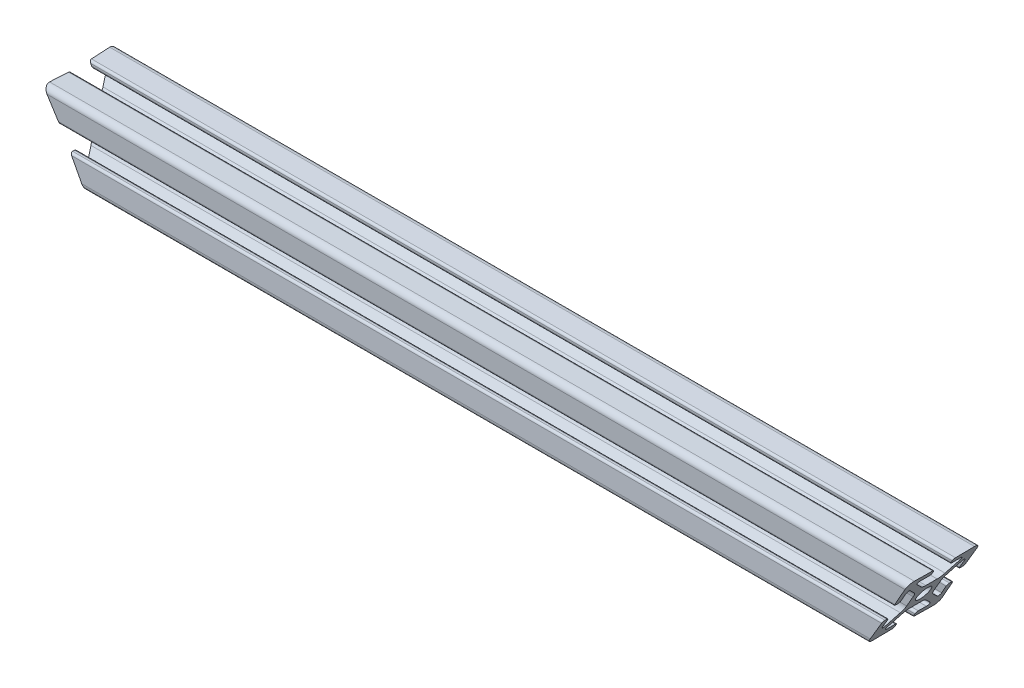
SolidWorks part; units mm, degrees
material "6061-T6 (SS)"
ref_plane "Front Plane" through (0, 0, 0) normal (0, 0, 1) x (1, 0, 0)
ref_plane "Top Plane" through (0, 0, 0) normal (0, 1, 0) x (1, 0, 0)
ref_plane "Right Plane" through (0, 0, 0) normal (1, 0, 0) x (0, 0, -1)
sketch "Sketch1" plane through (0, 0, 0) normal (1, 0, 0) x (0, 0, -1)
  line L0 (0, -12.7) -> (0, 12.7) construction
  line L1 (-7.874, 12.7) -> (7.874, 12.7) construction
  line L2 (-12.7, 0) -> (12.7, 0) construction
  line L3 (-7.874, 12.7) -> (-7.874, 4.826) construction
  line L4 (-3.302, 12.7) -> (3.302, 12.7) construction
  line L5 (-12.7, -12.7) -> (12.7, -12.7) construction
  line L6 (-12.7, 12.7) -> (12.7, 12.7) construction
  circle A0 centre (0, 0) radius 2.54 construction
  point P7 (0, 12.7)
  point P10 (0, 0)
  point P13 (0, 0)
  point P16 (0, 12.7)
  point P17 (-3.302, 12.7)
  point P18 (3.302, 12.7)
  point P21 (0, -12.7)
  point P24 (0, 12.7)
  dimension "Center Hole Diameter" = 5.08
  dimension "Rail Width" = 25.4
  dimension "Rail Height" = 25.4
  dimension "T-Slot Depth" = 7.874
  dimension "D1" = 15.748
  dimension "T-Slot Width" = 6.604
  dimension "D2" = 12.7
sketch "Sketch2" plane through (0, 0, 0) normal (0, 0, 1) x (1, 0, 0)
  line L0 (-152.4, 0) -> (152.4, 0) construction
  line L1 (0, 0) -> (0, 26.104) construction
  line L2 (152.4, -12.7) -> (152.4, 12.7) construction
  line L3 (-152.4, -12.7) -> (-152.4, 12.7) construction
  point P3 (-114.3, 0)
  point P8 (0, 0)
  point P9 (114.3, 0)
  point P12 (152.4, 0)
  point P15 (-152.4, 0)
  dimension "Length" = 304.8
  dimension "D1" = 38.1
  dimension "D2" = 25.4
sketch "Sketch3" plane through (0, 0, 0) normal (1, 0, 0) x (0, 0, -1)
  line L0 (0, 4.826) -> (1.9842, 4.826)
  line L1 (0, -12.7) -> (0, 12.7) construction
  line L2 (4.2293, 5.7559) -> (7.5866, 9.1132)
  line L6 (7.0212, 10.4136) -> (4.0906, 10.3112)
  line L7 (3.302, 11.0728) -> (3.302, 11.7082)
  line L8 (-7.874, 12.7) -> (7.874, 12.7) construction
  line L10 (0, 0) -> (12.7, 12.7) construction
  line L13 (0, 4.826) -> (0, 2.54)
  line L14 (4.826, 0) -> (2.54, 0)
  line L31 (4.826, 0) -> (4.826, 1.9842)
  line L32 (4.0374, 12.4697) -> (10.5971, 12.6988)
  line L33 (-12.7, 0) -> (12.7, 0) construction
  line L34 (-12.7, 12.7) -> (12.7, 12.7) construction
  line L35 (5.7559, 4.2293) -> (9.1132, 7.5866)
  line L36 (0, 12.7) -> (12.7, 12.7) construction
  line L37 (12.7, 12.7) -> (12.7, 8.0234) construction
  line L38 (11.0728, 3.302) -> (11.7082, 3.302)
  line L39 (10.4136, 7.0212) -> (10.3112, 4.0906)
  line L40 (12.6988, 10.5971) -> (12.4697, 4.0374)
  arc A0 (2.54, 0) -> (0, 2.54) centre (0, 0) ccw
  arc A1 (1.9842, 4.826) -> (4.2293, 5.7559) centre (1.9842, 8.001) ccw
  circle A2 centre (0, 0) radius 2.54 construction
  arc A7 (3.302, 11.7082) -> (4.0374, 12.4697) centre (4.064, 11.7082) cw
  arc A8 (4.0906, 10.3112) -> (3.302, 11.0728) centre (4.064, 11.0728) cw
  arc A14 (4.826, 1.9842) -> (5.7559, 4.2293) centre (8.001, 1.9842) cw
  arc A16 (10.5971, 12.6988) -> (12.6988, 10.5971) centre (10.668, 10.668) cw
  arc A17 (7.0212, 10.4136) -> (7.5866, 9.1132) centre (7.0478, 9.652) cw
  arc A18 (10.4136, 7.0212) -> (9.1132, 7.5866) centre (9.652, 7.0478) ccw
  arc A19 (10.3112, 4.0906) -> (11.0728, 3.302) centre (11.0728, 4.064) ccw
  arc A20 (11.7082, 3.302) -> (12.4697, 4.0374) centre (11.7082, 4.064) ccw
  point P37 (3.2994, 4.826)
  point P49 (12.7, 3.302)
  point P52 (3.302, 12.7)
  point P55 (3.302, 10.2837)
  dimension "D4" = 3.175
  dimension "D9" = 2.159
  dimension "D12" = 0.762
  dimension "D3" = 2.032
  dimension "D8" = 0.762
  dimension "D2" = 45
  dimension "D5" = 2
  dimension "D6" = 45
  dimension "D7" = 2.159
extrude "Boss-Extrude1" add sketch "Sketch3" against normal up to vertex (152.4 mm away) and the other way up to vertex (152.4 mm away) up to point (-152.4, 0, 0) other way up to point (152.4, 0, 0)
mirror "Mirror1" about plane through (0, 0, 0) normal (0, 1, 0) of bodies 104
mirror "Mirror2" about plane through (0, 0, 0) normal (0, 0, 1) of bodies 105
sketch "Sketch4" plane through (0, 0, 0) normal (0, 0, 1) x (1, 0, 0)
  line L1 (-154.94, -38.1) -> (154.94, -38.1)
  line L3 (152.4, 12.7) -> (137.7353, -12.7)
  line L4 (137.7353, -12.7) -> (-137.7353, -12.7)
  line L5 (-137.7353, -12.7) -> (-152.4, 12.7)
  line L6 (-152.4, 12.7) -> (-154.94, 12.7)
  line L7 (-154.94, 12.7) -> (-154.94, -38.1)
  line L8 (152.4, 12.7) -> (154.94, 12.7)
  line L9 (154.94, 12.7) -> (154.94, -38.1)
  dimension "D2" = 25.4
  dimension "D4" = 25.4
  dimension "D1" = 2.54
  dimension "D3" = 2.54
  dimension "D5" = 30
  dimension "D6" = 30
extrude "Cut-Extrude1" cut sketch "Sketch4" along normal blind 12.7 and the other way blind 12.7 contours L1 L9 L8 L3 L4 L5 L6 L7
ref_plane "Plane1" through (0, 0, 12.6988) normal (0, 0, -1) x (-1, 0, 0)
ref_plane "Plane2" through (0, -12.6988, 0) normal (0, -1, 0) x (-1, 0, 0)
ref_plane "Plane3" through (0, 12.6988, 0) normal (0, -1, 0) x (-1, 0, 0)
ref_plane "Plane4" through (0, 0, -12.6988) normal (0, 0, -1) x (-1, 0, 0)
equation "\"D1@Sketch2\"=\"Rail Height@Sketch1\"*1.5"
equation "\"D2@Sketch2\"=\"Rail Height@Sketch1\""
equation "\"MaxLength\"= \"FaceWidth@Assem2.SLDASM\""
equation "\"Length@Sketch2\"= \"MaxLength\""
equation "\"LeftCutAngle\"= \"RightCutAngle\""
equation "\"RightCutAngle\"= 45 - ( \"Phi@Assem2.SLDASM\" / 2 )"
equation "\"BarThickness\"= 1in"
equation "\"InnerLength\"= \"MaxLength\" - TAN ( \"LeftCutAngle\" ) - TAN ( \"RightCutAngle\" )"
equation "\"RightBevelLength\"= 0deg"
equation "\"D2@Sketch4\"=\"BarThickness\""
equation "\"D4@Sketch4\"=\"BarThickness\""
equation "\"D1@Cut-Extrude1\"=\"BarThickness\"/2"
equation "\"D2@Cut-Extrude1\"=\"BarThickness\"/2"
equation "\"D5@Sketch4\"=\"LeftCutAngle\""
equation "\"D6@Sketch4\"=\"RightCutAngle\""
